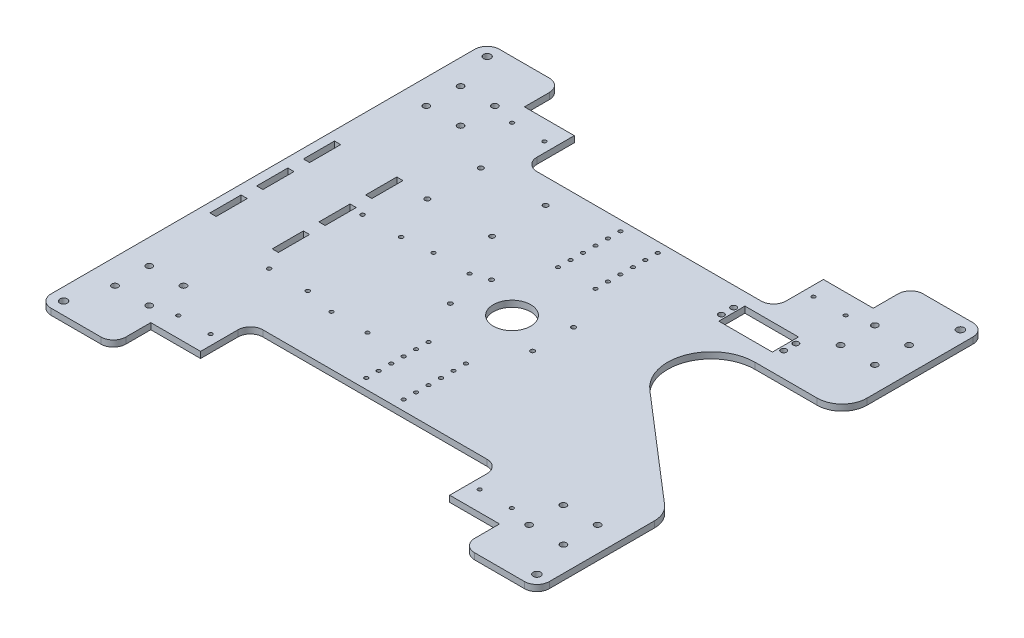
SolidWorks part; units mm, degrees
ref_plane "前基準面" through (0, 0, 0) normal (0, 0, 1) x (1, 0, 0)
ref_plane "上基準面" through (0, 0, 0) normal (0, 1, 0) x (1, 0, 0)
ref_plane "右基準面" through (0, 0, 0) normal (1, 0, 0) x (0, 0, -1)
sketch "草圖4" plane through (0, 0, 0) normal (0, 1, 0) x (1, 0, 0)
  line L0 (-200, 180) -> (-140, 180)
  line L1 (-140, 180) -> (-140, 150)
  line L2 (-140, 150) -> (-100, 150)
  line L3 (-100, 150) -> (-100, 110)
  line L4 (-100, 110) -> (100, 110)
  line L5 (100, 110) -> (100, 150)
  line L6 (100, 150) -> (140, 150)
  line L7 (140, 150) -> (140, 180)
  line L8 (140, 180) -> (200, 180)
  line L9 (-200, 180) -> (-200, -180)
  line L10 (-200, -180) -> (-140, -180)
  line L11 (-140, -180) -> (-140, -150)
  line L12 (-140, -150) -> (-100, -150)
  line L13 (-100, -150) -> (-100, -110)
  line L14 (-100, -110) -> (100, -110)
  line L15 (100, -110) -> (100, -150)
  line L16 (100, -150) -> (140, -150)
  line L17 (140, -150) -> (140, -180)
  line L18 (140, -180) -> (200, -180)
  line L19 (200, -180) -> (200, 180)
  line L20 (-100, 150) -> (100, 150) construction
  line L22 (100, -150) -> (-100, -150) construction
  line L24 (-140, 180) -> (140, 180) construction
  line L25 (140, -180) -> (-140, -180) construction
  line L27 (-100, 110) -> (100, -110) construction
  circle A0 centre (0, 0) radius 15
  dimension "D9" = 30
  dimension "D1" = 40
  dimension "D2" = 60
  dimension "D3" = 200
  dimension "D4" = 30
  dimension "D5" = 70
  dimension "D6" = 360
  dimension "D7" = 60
  dimension "D8" = 40
extrude "伸長1" add sketch "草圖4" along normal blind 5
sketch "草圖6" plane through (0, 5, 0) normal (0, 1, 0) x (-1, 0, 0)
  line L0 (200, -180) -> (200, 180) construction
  line L1 (115, -90) -> (63, -90) construction
  line L2 (115, -90) -> (115, -47) construction
  line L3 (115, -47) -> (63, -47) construction
  line L4 (63, -90) -> (63, -47) construction
  line L5 (115, -90) -> (63, -47) construction
  line L6 (115, -47) -> (63, -90) construction
  line L7 (75, -12) -> (46, -12) construction
  line L8 (75, -12) -> (75, 70) construction
  line L9 (75, 70) -> (46, 70) construction
  line L10 (46, -12) -> (46, 70) construction
  line L11 (75, -12) -> (46, 70) construction
  line L12 (75, 70) -> (46, -12) construction
  line L13 (33, -16.5) -> (-33, -16.5) construction
  line L14 (33, -16.5) -> (33, 16.5) construction
  line L15 (33, 16.5) -> (-33, 16.5) construction
  line L16 (-33, -16.5) -> (-33, 16.5) construction
  line L17 (33, -16.5) -> (-33, 16.5) construction
  line L18 (33, 16.5) -> (-33, -16.5) construction
  line L19 (130, -10) -> (99, -10) construction
  line L20 (130, -10) -> (130, 65) construction
  line L21 (130, 65) -> (99, 65) construction
  line L22 (99, -10) -> (99, 65) construction
  line L23 (130, -10) -> (99, 65) construction
  line L24 (130, 65) -> (99, -10) construction
  line L25 (100, 110) -> (-100, 110) construction
  line L26 (-100, -110) -> (100, -110) construction
  circle A0 centre (75, -12) radius 1.5
  circle A1 centre (46, -12) radius 1.5
  circle A2 centre (46, 70) radius 1.5
  circle A3 centre (75, 70) radius 1.5
  circle A4 centre (63, -90) radius 2
  circle A5 centre (115, -90) radius 2
  circle A6 centre (115, -47) radius 2
  circle A7 centre (63, -47) radius 2
  circle A8 centre (130, -10) radius 1.6
  circle A9 centre (130, 65) radius 1.6
  circle A10 centre (99, 65) radius 1.6
  circle A11 centre (99, -10) radius 1.6
  circle A12 centre (33, 16.5) radius 1.75
  circle A13 centre (33, -16.5) radius 1.75
  circle A14 centre (-33, -16.5) radius 1.75
  circle A15 centre (-33, 16.5) radius 1.75
  point P0 (89, -68.5)
  point P5 (60.5, 29)
  point P10 (0, 0)
  point P15 (114.5, 27.5)
  dimension "D1" = 29
  dimension "D3" = 3
  dimension "D4" = 4
  dimension "D7" = 3.2
  dimension "D10" = 3.5
  dimension "D2" = 82
  dimension "D5" = 52
  dimension "D6" = 43
  dimension "D8" = 31
  dimension "D9" = 75
  dimension "D11" = 66
  dimension "D12" = 33
  dimension "D13" = 70
  dimension "D14" = 125
  dimension "D15" = 85
  dimension "D16" = 45
  dimension "D17" = 40
  dimension "D18" = 20
extrude "伸長2" cut sketch "草圖6" against normal blind 5
sketch "草圖7" plane through (0, 5, 0) normal (0, 1, 0) x (1, 0, 0)
  line L0 (15, -92) -> (-15, -92) construction
  line L1 (15, -102) -> (-15, -102) construction
  line L2 (15, -102) -> (15, -52) construction
  line L3 (15, -52) -> (-15, -52) construction
  line L4 (-15, -102) -> (-15, -52) construction
  line L5 (15, -102) -> (-15, -52) construction
  line L6 (15, -52) -> (-15, -102) construction
  line L7 (-15, -82) -> (15, -82) construction
  line L8 (15, -72) -> (-15, -72) construction
  line L9 (-15, -62) -> (15, -62) construction
  line L10 (15, 62) -> (-15, 62) construction
  line L11 (15, 52) -> (-15, 52) construction
  line L12 (15, 52) -> (15, 102) construction
  line L13 (15, 102) -> (-15, 102) construction
  line L14 (-15, 52) -> (-15, 102) construction
  line L15 (15, 52) -> (-15, 102) construction
  line L16 (15, 102) -> (-15, 52) construction
  line L17 (-15, 72) -> (15, 72) construction
  line L18 (15, 82) -> (-15, 82) construction
  line L19 (-15, 92) -> (15, 92) construction
  line L20 (0, 77) -> (0, -77) construction
  line L21 (-100, -110) -> (100, -110) construction
  circle A0 centre (-15, -102) radius 1.5
  circle A1 centre (-15, -92) radius 1.5
  circle A2 centre (-15, -82) radius 1.5
  circle A3 centre (-15, -72) radius 1.5
  circle A4 centre (-15, -62) radius 1.5
  circle A5 centre (-15, -52) radius 1.5
  circle A6 centre (15, -102) radius 1.5
  circle A7 centre (15, -92) radius 1.5
  circle A8 centre (15, -72) radius 1.5
  circle A9 centre (15, -62) radius 1.5
  circle A10 centre (15, -52) radius 1.5
  circle A11 centre (15, -82) radius 1.5
  circle A12 centre (-15, 52) radius 1.5
  circle A13 centre (-15, 62) radius 1.5
  circle A14 centre (-15, 72) radius 1.5
  circle A15 centre (-15, 82) radius 1.5
  circle A16 centre (-15, 92) radius 1.5
  circle A17 centre (-15, 102) radius 1.5
  circle A18 centre (15, 52) radius 1.5
  circle A19 centre (15, 62) radius 1.5
  circle A20 centre (15, 82) radius 1.5
  circle A21 centre (15, 92) radius 1.5
  circle A22 centre (15, 102) radius 1.5
  circle A23 centre (15, 72) radius 1.5
  point P0 (0, -77)
  point P25 (37.8027, -51.0899)
  point P26 (0, 77)
  dimension "D13" = 3
  dimension "D14" = 3
  dimension "D1" = 10
  dimension "D2" = 10
  dimension "D3" = 10
  dimension "D4" = 10
  dimension "D5" = 10
  dimension "D6" = 30
  dimension "D7" = 50
  dimension "D8" = 30
  dimension "D9" = 10
  dimension "D10" = 10
  dimension "D11" = 10
  dimension "D12" = 10
  dimension "D15" = 8
extrude "伸長3" cut sketch "草圖7" against normal through all
sketch "草圖8" plane through (0, 5, 0) normal (0, 1, 0) x (1, 0, 0)
  line L0 (-140, 180) -> (-200, 180) construction
  line L1 (190, 170) -> (-190, 170) construction
  line L2 (190, 170) -> (190, -170) construction
  line L3 (190, -170) -> (-190, -170) construction
  line L4 (-190, 170) -> (-190, -170) construction
  line L5 (190, 170) -> (-190, -170) construction
  line L6 (190, -170) -> (-190, 170) construction
  line L7 (-200, 180) -> (-200, -180) construction
  circle A0 centre (190, 170) radius 3
  circle A1 centre (-190, 170) radius 3
  circle A2 centre (-190, -170) radius 3
  circle A3 centre (190, -170) radius 3
  point P8 (0, 0)
  dimension "D1" = 6
  dimension "D2" = 10
  dimension "D3" = 10
extrude "伸長4" cut sketch "草圖8" against normal blind 10
sketch "草圖10" plane through (0, 5, 0) normal (0, 1, 0) x (1, 0, 0)
  line L0 (-187.5, 50) -> (-142.5, 50) construction
  line L1 (-137.5, -50) -> (-142.5, -50)
  line L2 (-137.5, -50) -> (-137.5, -25)
  line L3 (-137.5, -25) -> (-142.5, -25)
  line L4 (-142.5, -50) -> (-142.5, -25)
  line L5 (-187.5, -50) -> (-192.5, -50)
  line L6 (-187.5, -50) -> (-187.5, -25)
  line L7 (-187.5, -25) -> (-192.5, -25)
  line L8 (-192.5, -50) -> (-192.5, -25)
  line L9 (-137.5, 25) -> (-142.5, 25)
  line L10 (-137.5, 25) -> (-137.5, 50)
  line L11 (-137.5, 50) -> (-142.5, 50)
  line L12 (-142.5, 25) -> (-142.5, 50)
  line L13 (-187.5, 25) -> (-192.5, 25)
  line L14 (-187.5, 25) -> (-187.5, 50)
  line L15 (-187.5, 50) -> (-192.5, 50)
  line L16 (-192.5, 25) -> (-192.5, 50)
  line L17 (-187.5, -25) -> (-142.5, -25) construction
  line L18 (-192.5, 25) -> (-192.5, -25) construction
  line L19 (-142.5, 25) -> (-142.5, -25) construction
  line L20 (-187.5, 25) -> (-142.5, 25) construction
  line L21 (-187.5, -50) -> (-142.5, -50) construction
  line L22 (-187.5, 25) -> (-187.5, -25) construction
  line L23 (-137.5, 25) -> (-137.5, -25) construction
  line L24 (-187.5, 12.5) -> (-142.5, 12.5) construction
  line L25 (-192.5, 12.5) -> (-187.5, 12.5)
  line L26 (-192.5, 12.5) -> (-192.5, -12.5)
  line L27 (-192.5, -12.5) -> (-187.5, -12.5)
  line L28 (-187.5, 12.5) -> (-187.5, -12.5)
  line L29 (-142.5, 12.5) -> (-137.5, 12.5)
  line L30 (-142.5, 12.5) -> (-142.5, -12.5)
  line L31 (-142.5, -12.5) -> (-137.5, -12.5)
  line L32 (-137.5, 12.5) -> (-137.5, -12.5)
  line L33 (-187.5, -12.5) -> (-142.5, -12.5) construction
  line L34 (-187.5, 12.5) -> (-142.5, -12.5) construction
  line L35 (-187.5, -12.5) -> (-142.5, 12.5) construction
  line L36 (-165, 0) -> (0, 0) construction
  dimension "D1" = 25
  dimension "D2" = 5
  dimension "D3" = 45
  dimension "D4" = 100
  dimension "D5" = 12.5
  dimension "D6" = 165
extrude "伸長6" cut sketch "草圖10" against normal blind 10
sketch "草圖12" plane through (0, 5, 0) normal (0, 1, 0) x (1, 0, 0)
  line L0 (135, 94.9) -> (135, 85.1) construction
  line L1 (139.5, 100) -> (180, 100)
  line L2 (139.5, 100) -> (139.5, 80)
  line L3 (139.5, 80) -> (180, 80)
  line L4 (180, 100) -> (180, 80)
  line L5 (139.5, 100) -> (180, 80) construction
  line L6 (139.5, 80) -> (180, 100) construction
  line L7 (184.5, 94.9) -> (184.5, 85.1) construction
  line L8 (135, 90) -> (184.5, 90) construction
  line L9 (135, 94.9) -> (184.5, 94.9) construction
  line L10 (135, -85.1) -> (135, -94.9) construction
  line L11 (139.5, -80) -> (180, -80)
  line L12 (139.5, -80) -> (139.5, -100)
  line L13 (139.5, -100) -> (180, -100)
  line L14 (180, -80) -> (180, -100)
  line L15 (139.5, -80) -> (180, -100) construction
  line L16 (139.5, -100) -> (180, -80) construction
  line L17 (184.5, -85.1) -> (184.5, -94.9) construction
  line L18 (135, -90) -> (184.5, -90) construction
  line L19 (135, -85.1) -> (184.5, -85.1) construction
  line L20 (159.75, 90) -> (159.75, -90) construction
  line L21 (0, 0) -> (159.75, 0) construction
  line L22 (200, -180) -> (200, 180) construction
  line L23 (200, 180) -> (140, 180) construction
  circle A0 centre (135, 94.9) radius 2.25
  circle A1 centre (135, 85.1) radius 2.25
  circle A2 centre (184.5, 94.9) radius 2.25
  circle A3 centre (184.5, 85.1) radius 2.25
  circle A4 centre (135, -85.1) radius 2.25
  circle A5 centre (135, -94.9) radius 2.25
  circle A6 centre (184.5, -85.1) radius 2.25
  circle A7 centre (184.5, -94.9) radius 2.25
  point P0 (159.75, 90)
  point P15 (159.75, -90)
  dimension "D1" = 4.5
  dimension "D6" = 4.5
  dimension "D2" = 40.5
  dimension "D3" = 20
  dimension "D4" = 9.8
  dimension "D5" = 4.5
  dimension "D7" = 40.5
  dimension "D8" = 20
  dimension "D9" = 9.8
  dimension "D10" = 4.5
  dimension "D11" = 20
  dimension "D12" = 80
extrude "伸長7" [suppressed] cut sketch "草圖12" against normal blind 10
sketch "草圖13" plane through (0, 5, 0) normal (0, 1, 0) x (-1, 0, 0)
  line L0 (-152.5, -138.75) -> (-180, -138.75) construction
  line L1 (180, -138.75) -> (152.5, -138.75) construction
  line L2 (180, -138.75) -> (180, -111.25) construction
  line L3 (180, -111.25) -> (152.5, -111.25) construction
  line L4 (152.5, -138.75) -> (152.5, -111.25) construction
  line L5 (180, -138.75) -> (152.5, -111.25) construction
  line L6 (180, -111.25) -> (152.5, -138.75) construction
  line L7 (-152.5, -138.75) -> (-152.5, -111.25) construction
  line L8 (-152.5, -111.25) -> (-180, -111.25) construction
  line L9 (-180, -138.75) -> (-180, -111.25) construction
  line L10 (-152.5, -138.75) -> (-180, -111.25) construction
  line L11 (-152.5, -111.25) -> (-180, -138.75) construction
  line L12 (180, 111.25) -> (152.5, 111.25) construction
  line L13 (180, 111.25) -> (180, 138.75) construction
  line L14 (180, 138.75) -> (152.5, 138.75) construction
  line L15 (152.5, 111.25) -> (152.5, 138.75) construction
  line L16 (180, 111.25) -> (152.5, 138.75) construction
  line L17 (180, 138.75) -> (152.5, 111.25) construction
  line L18 (-152.5, 111.25) -> (-180, 111.25) construction
  line L19 (-152.5, 111.25) -> (-152.5, 138.75) construction
  line L20 (-152.5, 138.75) -> (-180, 138.75) construction
  line L21 (-180, 111.25) -> (-180, 138.75) construction
  line L22 (-152.5, 111.25) -> (-180, 138.75) construction
  line L23 (-152.5, 138.75) -> (-180, 111.25) construction
  line L24 (-200, 180) -> (-200, -180) construction
  line L25 (166.25, -125) -> (-166.25, -125) construction
  line L26 (166.25, -125) -> (166.25, 125) construction
  line L27 (166.25, 125) -> (-166.25, 125) construction
  line L28 (-166.25, -125) -> (-166.25, 125) construction
  line L29 (166.25, -125) -> (-166.25, 125) construction
  line L30 (166.25, 125) -> (-166.25, -125) construction
  line L31 (100, -150) -> (140, -150) construction
  circle A0 centre (180, -138.75) radius 2.5
  circle A1 centre (152.5, -138.75) radius 2.5
  circle A2 centre (152.5, -111.25) radius 2.5
  circle A3 centre (180, -111.25) radius 2.5
  circle A4 centre (-152.5, -138.75) radius 2.5
  circle A5 centre (-180, -138.75) radius 2.5
  circle A6 centre (-180, -111.25) radius 2.5
  circle A7 centre (-152.5, -111.25) radius 2.5
  circle A8 centre (180, 111.25) radius 2.5
  circle A9 centre (152.5, 111.25) radius 2.5
  circle A10 centre (152.5, 138.75) radius 2.5
  circle A11 centre (180, 138.75) radius 2.5
  circle A12 centre (-152.5, 111.25) radius 2.5
  circle A13 centre (-180, 111.25) radius 2.5
  circle A14 centre (-180, 138.75) radius 2.5
  circle A15 centre (-152.5, 138.75) radius 2.5
  point P0 (166.25, -125)
  point P9 (-166.25, -125)
  point P18 (166.25, 125)
  point P27 (-166.25, 125)
  point P36 (0, 0)
  dimension "D1" = 5
  dimension "D2" = 27.5
  dimension "D3" = 27.5
  dimension "D4" = 27.5
  dimension "D5" = 27.5
  dimension "D6" = 27.5
  dimension "D7" = 27.5
  dimension "D8" = 27.5
  dimension "D9" = 27.5
  dimension "D10" = 20
  dimension "D11" = 25
extrude "伸長8" cut sketch "草圖13" against normal blind 10
sketch "草圖14" plane through (0, 5, 0) normal (0, 1, 0) x (1, 0, 0)
  line L0 (200, 0) -> (280, 0) construction
  line L1 (200, -180) -> (200, 180) construction
  circle A0 centre (280, 0) radius 100
  dimension "D1" = 200
  dimension "D2" = 80
extrude "伸長9" [suppressed] cut sketch "草圖14" against normal blind 10
sketch "草圖15" plane through (0, 5, 0) normal (0, 1, 0) x (1, 0, 0)
  line L0 (155, 5) -> (165, 5) construction
  line L1 (115, 5) -> (125, 5) construction
  line L2 (115, 5) -> (115, -5) construction
  line L3 (115, -5) -> (125, -5) construction
  line L4 (125, 5) -> (125, -5) construction
  line L5 (115, 5) -> (125, -5) construction
  line L6 (115, -5) -> (125, 5) construction
  line L7 (155, 5) -> (155, -5) construction
  line L8 (155, -5) -> (165, -5) construction
  line L9 (165, 5) -> (165, -5) construction
  line L10 (155, 5) -> (165, -5) construction
  line L11 (155, -5) -> (165, 5) construction
  line L12 (135, 5) -> (145, 5) construction
  line L13 (135, 5) -> (135, -5) construction
  line L14 (135, -5) -> (145, -5) construction
  line L15 (145, 5) -> (145, -5) construction
  line L16 (135, 5) -> (145, -5) construction
  line L17 (135, -5) -> (145, 5) construction
  line L18 (120, 0) -> (140, 0) construction
  line L19 (140, 0) -> (160, 0) construction
  line L20 (120, 0) -> (0, 0) construction
  circle A0 centre (125, 5) radius 1.5
  circle A1 centre (125, -5) radius 1.5
  circle A2 centre (115, 5) radius 1.5
  circle A3 centre (115, -5) radius 1.5
  circle A4 centre (165, 5) radius 1.5
  circle A5 centre (165, -5) radius 1.5
  circle A6 centre (155, 5) radius 1.5
  circle A7 centre (155, -5) radius 1.5
  circle A8 centre (145, 5) radius 1.5
  circle A9 centre (145, -5) radius 1.5
  circle A10 centre (135, 5) radius 1.5
  circle A11 centre (135, -5) radius 1.5
  point P0 (120, 0)
  point P9 (128.8119, 3.5381)
  point P10 (160, 0)
  point P19 (202.378, -1.6151)
  point P20 (140, 0)
  point P29 (344.3803, 3.9326)
  dimension "D1" = 3
  dimension "D4" = 3
  dimension "D7" = 3
  dimension "D2" = 10
  dimension "D3" = 10
  dimension "D5" = 10
  dimension "D6" = 10
  dimension "D8" = 10
  dimension "D9" = 10
  dimension "D10" = 10
  dimension "D11" = 10
  dimension "D12" = 120
extrude "伸長10" [suppressed] cut sketch "草圖15" against normal blind 10
sketch "草圖17" plane through (0, 5, 0) normal (0, 1, 0) x (-1, 0, 0)
  line L0 (-108, -134) -> (-133.89, -134) construction
  line L1 (-140, -150) -> (-100, -150) construction
  line L2 (-100, -150) -> (-100, -110) construction
  line L3 (-108, 134) -> (-133.89, 134) construction
  line L4 (133.89, -134) -> (108, -134) construction
  line L5 (133.89, 134) -> (108, 134) construction
  line L6 (133.89, -134) -> (133.89, 134) construction
  line L7 (133.89, 134) -> (-108, 134) construction
  line L8 (-108, 134) -> (-108, -134) construction
  line L9 (-108, -134) -> (133.89, -134) construction
  line L10 (100, -110) -> (100, -150) construction
  line L11 (140, 150) -> (100, 150) construction
  circle A0 centre (-108, -134) radius 1.5
  circle A1 centre (-133.89, -134) radius 1.5
  circle A2 centre (-108, 134) radius 1.5
  circle A3 centre (-133.89, 134) radius 1.5
  circle A4 centre (133.89, -134) radius 1.5
  circle A5 centre (108, -134) radius 1.5
  circle A6 centre (133.89, 134) radius 1.5
  circle A7 centre (108, 134) radius 1.5
  dimension "D1" = 3
  dimension "D8" = 3
  dimension "D9" = 3
  dimension "D10" = 3
  dimension "D2" = 25.89
  dimension "D3" = 16
  dimension "D4" = 8
  dimension "D5" = 25.89
  dimension "D6" = 25.89
  dimension "D7" = 25.89
  dimension "D11" = 8
  dimension "D12" = 16
extrude "伸長11" cut sketch "草圖17" against normal blind 10
sketch "草圖18" plane through (0, 5, 0) normal (0, 1, 0) x (-1, 0, 0)
  line L0 (160, -70) -> (176, -70) construction
  line L1 (163, -70) -> (160, -70)
  line L2 (163, -70) -> (163, -60)
  line L3 (163, -60) -> (160, -60)
  line L4 (160, -70) -> (160, -60)
  line L5 (176, -70) -> (173, -70)
  line L6 (176, -70) -> (176, -60)
  line L7 (176, -60) -> (173, -60)
  line L8 (173, -70) -> (173, -60)
  line L9 (176, -60) -> (160, -60) construction
  line L10 (160, -5) -> (176, -5) construction
  line L11 (163, -5) -> (160, -5)
  line L12 (163, -5) -> (163, 5)
  line L13 (163, 5) -> (160, 5)
  line L14 (160, -5) -> (160, 5)
  line L15 (176, -5) -> (173, -5)
  line L16 (176, -5) -> (176, 5)
  line L17 (176, 5) -> (173, 5)
  line L18 (173, -5) -> (173, 5)
  line L19 (176, 5) -> (160, 5) construction
  line L20 (160, 60) -> (176, 60) construction
  line L21 (163, 60) -> (160, 60)
  line L22 (163, 60) -> (163, 70)
  line L23 (163, 70) -> (160, 70)
  line L24 (160, 60) -> (160, 70)
  line L25 (176, 60) -> (173, 60)
  line L26 (176, 60) -> (176, 70)
  line L27 (176, 70) -> (173, 70)
  line L28 (173, 60) -> (173, 70)
  line L29 (176, 70) -> (160, 70) construction
  line L30 (40, -43) -> (40, -33) construction
  line L31 (40, -46) -> (30, -46)
  line L32 (40, -46) -> (40, -43)
  line L33 (40, -43) -> (30, -43)
  line L34 (30, -46) -> (30, -43)
  line L35 (40, -33) -> (30, -33)
  line L36 (40, -33) -> (40, -30)
  line L37 (40, -30) -> (30, -30)
  line L38 (30, -33) -> (30, -30)
  line L39 (100, 83) -> (100, 93) construction
  line L40 (30, -43) -> (30, -33) construction
  line L41 (100, 80) -> (90, 80)
  line L42 (100, 80) -> (100, 83)
  line L43 (100, 83) -> (90, 83)
  line L44 (90, 80) -> (90, 83)
  line L45 (100, 93) -> (90, 93)
  line L46 (100, 93) -> (100, 96)
  line L47 (100, 96) -> (90, 96)
  line L48 (90, 93) -> (90, 96)
  line L49 (90, 83) -> (90, 93) construction
  line L50 (140, -43) -> (140, -33) construction
  line L51 (140, -46) -> (130, -46)
  line L52 (140, -46) -> (140, -43)
  line L53 (140, -43) -> (130, -43)
  line L54 (130, -46) -> (130, -43)
  line L55 (140, -33) -> (130, -33)
  line L56 (140, -33) -> (140, -30)
  line L57 (140, -30) -> (130, -30)
  line L58 (130, -33) -> (130, -30)
  line L59 (130, -43) -> (130, -33) construction
  line L60 (176, -60) -> (176, -5) construction
  line L61 (176, 60) -> (176, 5) construction
  line L62 (130, -46) -> (40, -46) construction
  line L63 (160, 0) -> (0, 0) construction
  line L64 (200, -180) -> (200, 180) construction
  dimension "D1" = 3
  dimension "D2" = 10
  dimension "D3" = 10
  dimension "D4" = 3
  dimension "D5" = 10
  dimension "D6" = 3
  dimension "D7" = 10
  dimension "D8" = 3
  dimension "D9" = 3
  dimension "D10" = 10
  dimension "D11" = 10
  dimension "D12" = 10
  dimension "D13" = 10
  dimension "D14" = 3
  dimension "D15" = 3
  dimension "D16" = 10
  dimension "D17" = 10
  dimension "D18" = 3
  dimension "D19" = 3
  dimension "D20" = 10
  dimension "D21" = 10
  dimension "D22" = 55
  dimension "D23" = 160
  dimension "D24" = 90
  dimension "D25" = 30
  dimension "D26" = 30
  dimension "D27" = 110
  dimension "D28" = 100
extrude "伸長12" [suppressed] cut sketch "草圖18" against normal blind 10
fillet "圓角1" radius 10 12 edges at (200, 2.5, 180) (-100, 2.5, 110) (100, 2.5, 110) (140, 2.5, 180) (-140, 2.5, 180) (-200, 2.5, 180) (-200, 2.5, -180) (-140, 2.5, -180) (-100, 2.5, -110) (100, 2.5, -110) (140, 2.5, -180) (200, 2.5, -180)
sketch "草圖19" plane through (0, 5, 0) normal (0, 1, 0) x (1, 0, 0)
  line L0 (130, 65) -> (200, 65)
  line L2 (200, -170) -> (200, 170) construction
  line L3 (140, 150) -> (100, 150) construction
  line L4 (107.1537, 3.485) -> (200, -76.515)
  line L5 (200, -170) -> (200, 170) construction
  arc A0 (130, 65) -> (107.1537, 3.485) centre (130, 30) ccw
  dimension "D2" = 35
  dimension "D1" = 70
  dimension "D3" = 120
  dimension "D4" = 80
extrude "伸長13" cut sketch "草圖19" against normal through all and the other way through all
fillet "圓角2" radius 20 2 edges at (200, 2.5, -65) (200, 2.5, 76.515)
sketch "草圖21" plane through (0, 5, 0) normal (0, 1, 0) x (1, 0, 0)
  line L0 (140, 150) -> (100, 150) construction
  line L1 (83.5, 94.4) -> (133.5, 94.4) construction
  line L2 (83.5, 94.4) -> (83.5, 84.6) construction
  line L3 (83.5, 84.6) -> (133.5, 84.6) construction
  line L4 (133.5, 94.4) -> (133.5, 84.6) construction
  line L5 (83.5, 94.4) -> (133.5, 84.6) construction
  line L6 (83.5, 84.6) -> (133.5, 94.4) construction
  line L7 (87, 100) -> (130, 100)
  line L8 (87, 100) -> (87, 79)
  line L9 (87, 79) -> (130, 79)
  line L10 (130, 100) -> (130, 79)
  line L11 (87, 100) -> (130, 79) construction
  line L12 (87, 79) -> (130, 100) construction
  line L13 (200, 85) -> (200, 170) construction
  circle A0 centre (83.5, 94.4) radius 2.25
  circle A1 centre (83.5, 84.6) radius 2.25
  circle A2 centre (133.5, 84.6) radius 2.25
  circle A3 centre (133.5, 94.4) radius 2.25
  point P0 (108.5, 89.5)
  point P5 (108.5, 89.5)
  dimension "D1" = 4.5
  dimension "D2" = 9.8
  dimension "D3" = 43
  dimension "D4" = 50
  dimension "D5" = 21
  dimension "D6" = 50
  dimension "D7" = 70
extrude "伸長14" cut sketch "草圖21" against normal blind 10
